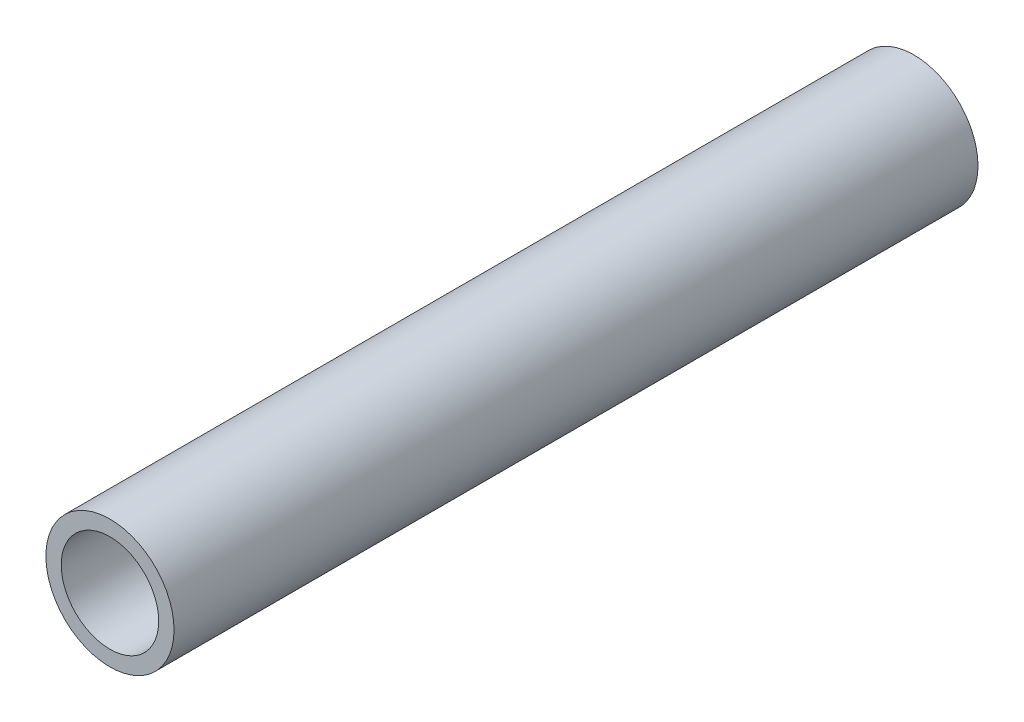
SolidWorks part; units mm, degrees
material "Plain Carbon Steel"
ref_plane "Front Plane" through (0, 0, 0) normal (0, 0, 1) x (1, 0, 0)
ref_plane "Top Plane" through (0, 0, 0) normal (0, 1, 0) x (1, 0, 0)
ref_plane "Right Plane" through (0, 0, 0) normal (1, 0, 0) x (0, 0, -1)
sketch "Sketch1" plane through (0, 0, 0) normal (0, 0, 1) x (1, 0, 0)
  circle A0 centre (0, 0) radius 12.7
  circle A1 centre (0, 0) radius 16.7005
extrude "Boss-Extrude1" add sketch "Sketch1" along normal blind 209.55
